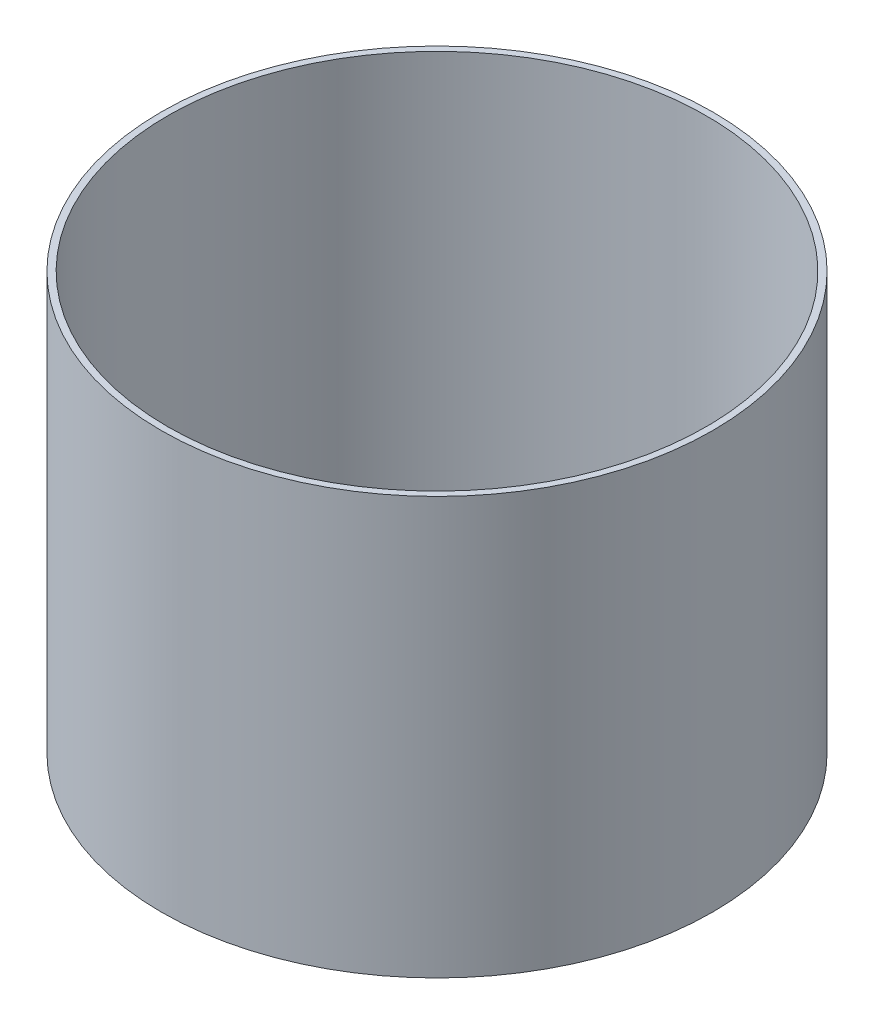
SolidWorks part; units mm, degrees
ref_plane "Front Plane" through (0, 0, 0) normal (0, 0, 1) x (1, 0, 0)
ref_plane "Top Plane" through (0, 0, 0) normal (0, 1, 0) x (1, 0, 0)
ref_plane "Right Plane" through (0, 0, 0) normal (1, 0, 0) x (0, 0, -1)
sketch "Sketch1" plane through (0, 0, 0) normal (0, 1, 0) x (1, 0, 0)
  circle A0 centre (0, 0) radius 7.75
  circle A1 centre (0, 0) radius 7.9375
  dimension "D1" = 15.5
  dimension "D2" = 15.875
extrude "Boss-Extrude1" add sketch "Sketch1" along normal blind 12
